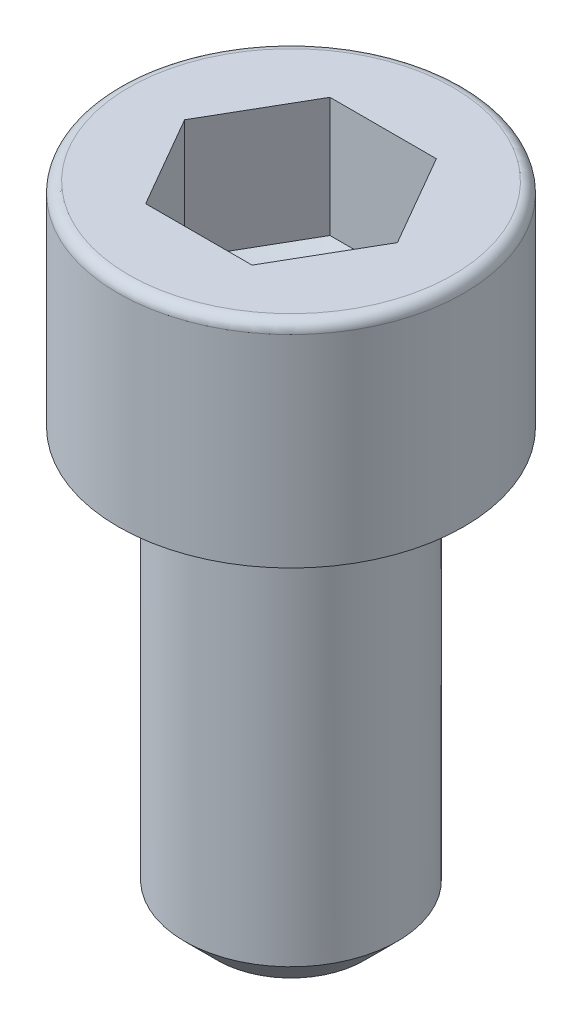
SolidWorks part; units mm, degrees
ref_plane "Front Plane" through (0, 0, 0) normal (0, 0, 1) x (1, 0, 0)
ref_plane "Top Plane" through (0, 0, 0) normal (0, 1, 0) x (1, 0, 0)
ref_plane "Right Plane" through (0, 0, 0) normal (1, 0, 0) x (0, 0, -1)
sketch "Sketch1" plane through (0, 0, 0) normal (0, 0, 1) x (1, 0, 0)
  line L0 (0, 0) -> (0, 24)
  line L1 (0, 24) -> (-6.5, 24)
  line L2 (-6.5, 24) -> (-6.5, 16)
  line L3 (-6.5, 16) -> (-4, 16)
  line L4 (-4, 16) -> (-4, 0)
  line L5 (-4, 0) -> (0, 0)
  line L6 (0, 0) -> (0, 37.8809) construction
  dimension "D1" = 6.5
  dimension "D2" = 4
  dimension "D3" = 8
  dimension "D4" = 16
revolve "Revolve1" add sketch "Sketch1" angle 360 about L0
chamfer "Chamfer1" distance 1.25 angle 45 1 edges at (0, 0, -4)
fillet "Fillet1" radius 0.4 1 edges at (0, 24, -6.5)
sketch "Sketch2" plane through (0, 24, 0) normal (0, 1, 0) x (1, 0, 0)
  line L1 (-4, 0) -> (-2, -3.4641)
  line L2 (-2, -3.4641) -> (2, -3.4641)
  line L3 (2, -3.4641) -> (4, 0)
  line L4 (4, 0) -> (2, 3.4641)
  line L5 (2, 3.4641) -> (-2, 3.4641)
  line L6 (-2, 3.4641) -> (-4, 0)
  circle A0 centre (0, 0) radius 3.4641 construction
  point P1 (0, 0)
  dimension "D1" = 4
extrude "Cut-Extrude1" cut sketch "Sketch2" against normal blind 4.5
sketch "Sketch3" plane through (0, 0, 0) normal (0, 0, 1) x (1, 0, 0)
  line L0 (4, 19.5) -> (0, 18.5)
  line L1 (0, 18.5) -> (0, 19.5)
  line L2 (-2, 19.5) -> (2, 19.5) construction
  line L3 (0, 19.5) -> (4, 19.5)
  line L4 (2, 19.5) -> (4, 19.5) construction
  point P2 (0, 0)
  point P6 (3.9958, 33.5)
  point P9 (0, 0)
  point P10 (0, 32.5)
  point P11 (2, 33.5)
  point P12 (4.0341, 33.5)
  dimension "D1" = 1
  dimension "D2" = 4
revolve "Cut-Revolve1" cut sketch "Sketch3" angle 360 about L1
